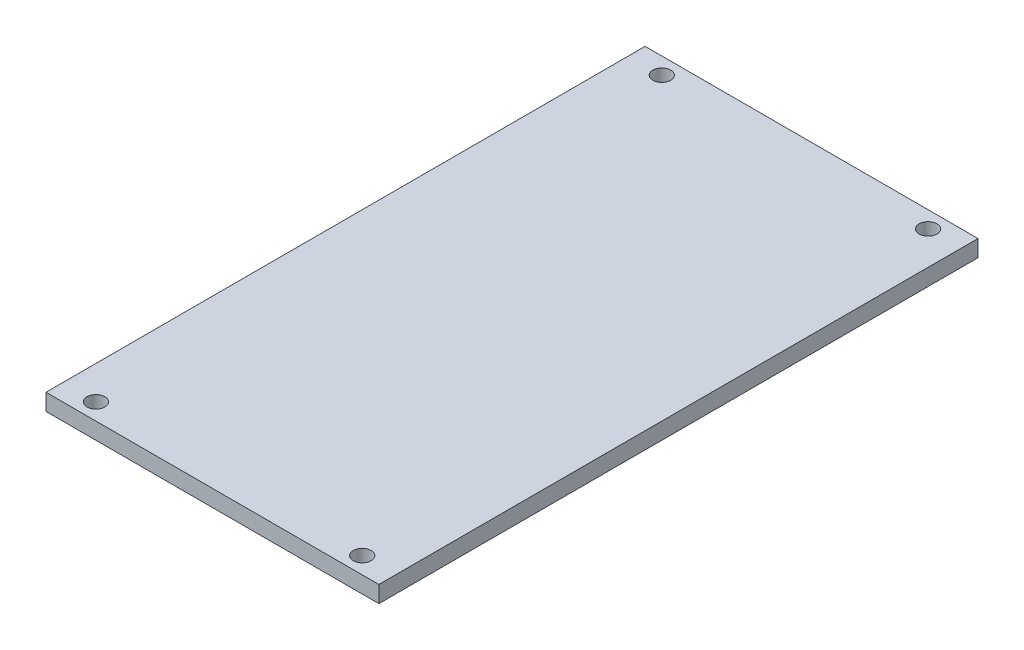
SolidWorks part; units mm, degrees
ref_plane "Front Plane" through (0, 0, 0) normal (0, 0, 1) x (1, 0, 0)
ref_plane "Top Plane" through (0, 0, 0) normal (0, 1, 0) x (1, 0, 0)
ref_plane "Right Plane" through (0, 0, 0) normal (1, 0, 0) x (0, 0, -1)
sketch "Sketch1" plane through (0, 0, 0) normal (0, 1, 0) x (1, 0, 0)
  line L1 (-31.75, 57.15) -> (31.75, 57.15)
  line L2 (-31.75, 57.15) -> (-31.75, -57.15)
  line L3 (-31.75, -57.15) -> (31.75, -57.15)
  line L4 (31.75, 57.15) -> (31.75, -57.15)
  line L5 (-31.75, 57.15) -> (31.75, -57.15) construction
  line L6 (-31.75, -57.15) -> (31.75, 57.15) construction
  point P0 (0, 0)
  dimension "D1" = 63.5
  dimension "D2" = 114.3
extrude "Boss-Extrude1" add sketch "Sketch1" along normal blind 3.175
sketch "Sketch2" plane through (0, 3.175, 0) normal (0, 1, 0) x (1, 0, 0)
  line L1 (25.4, -53.975) -> (-25.4, -53.975) construction
  line L2 (25.4, -53.975) -> (25.4, 53.975) construction
  line L3 (25.4, 53.975) -> (-25.4, 53.975) construction
  line L4 (-25.4, -53.975) -> (-25.4, 53.975) construction
  line L5 (25.4, -53.975) -> (-25.4, 53.975) construction
  line L6 (25.4, 53.975) -> (-25.4, -53.975) construction
  circle A0 centre (-25.4, 53.975) radius 1.7
  circle A1 centre (25.4, 53.975) radius 1.7
  point P0 (0, 0)
  dimension "D3" = 3.4
  dimension "D4" = 3.4
  dimension "D1" = 50.8
  dimension "D2" = 107.95
extrude "Cut-Extrude1" cut sketch "Sketch2" against normal through all
mirror "Mirror1" about plane through (0, 0, 0) normal (0, 0, 1) of "Cut-Extrude1"
